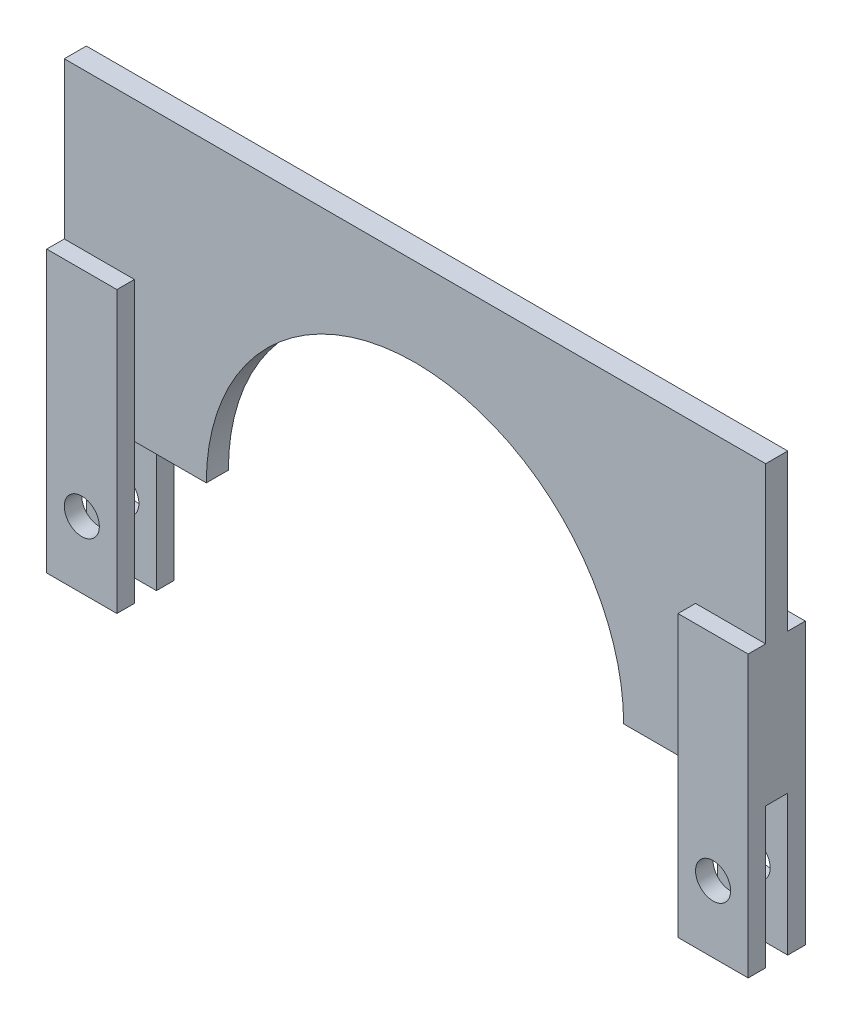
SolidWorks part; units mm, degrees
ref_plane "Front Plane" through (0, 0, 0) normal (0, 0, 1) x (1, 0, 0)
ref_plane "Top Plane" through (0, 0, 0) normal (0, 1, 0) x (1, 0, 0)
ref_plane "Right Plane" through (0, 0, 0) normal (1, 0, 0) x (0, 0, -1)
sketch "Sketch1" plane through (0, 0, 0) normal (0, 0, 1) x (1, 0, 0)
  line L0 (-25.4, 0) -> (-15.113, 0)
  line L1 (15.113, 0) -> (25.4, 0)
  line L2 (-25.4, 0) -> (-25.4, 21.463)
  line L3 (-25.4, 21.463) -> (25.4, 21.463)
  line L4 (25.4, 21.463) -> (25.4, 0)
  line L5 (0, 0) -> (7.308, 0) construction
  arc A0 (15.113, 0) -> (-15.113, 0) centre (0, 0) ccw
  point P4 (0, 15.113)
  point P7 (0, 0)
  dimension "D1" = 15.113
  dimension "D2" = 50.8
  dimension "D3" = 6.35
extrude "Boss-Extrude1" add sketch "Sketch1" along normal mid plane 1.5971
sketch "Sketch2" plane through (0, 0, 0.7986) normal (0, 0, 1) x (1, 0, 0)
  line L0 (25.4, 0) -> (20.32, 0)
  line L1 (15.113, 0) -> (25.4, 0) construction
  line L2 (25.4, 0) -> (25.4, -10.16)
  line L3 (25.4, -10.16) -> (20.32, -10.16)
  line L4 (20.32, -10.16) -> (20.32, 0)
  line L5 (20.32, 0) -> (20.32, 10.16)
  line L6 (20.32, 10.16) -> (25.4, 10.16)
  line L7 (25.4, 0) -> (25.4, 21.463) construction
  line L8 (25.4, 10.16) -> (25.4, 0)
  line M7 (15.113, 0) -> (25.4, 0)
  line M8 (25.4, 0) -> (25.4, 21.463)
  dimension "D1" = 5.08
  dimension "D2" = 10.16
extrude "Boss-Extrude3" add sketch "Sketch2" along normal blind 1.27 contours L6 L5 M7 M8 | L4 L3 L2 M7
mirror "Mirror1" about plane through (0, 0, 0) normal (0, 0, 1) of "Boss-Extrude3"
mirror "Mirror2" about plane through (0, 0, 0) normal (1, 0, 0) of "Mirror1", "Boss-Extrude3"
sketch "Sketch3" plane through (0, 0, -2.0686) normal (0, 0, -1) x (-1, 0, 0)
  line L0 (-25.4, 0) -> (-22.86, 0) construction
  line L1 (-25.4, -10.16) -> (-25.4, 10.16) construction
  line L2 (-25.4, 0) -> (-25.4, -5.334)
  circle A0 centre (-22.86, -5.334) radius 1.27
  dimension "D3" = 2.54
  dimension "D1" = 2.54
  dimension "D2" = 5.334
extrude "Cut-Extrude1" cut sketch "Sketch3" against normal through all contours A0
mirror "Mirror3" about plane through (0, 0, 0) normal (1, 0, 0) of "Cut-Extrude1"
